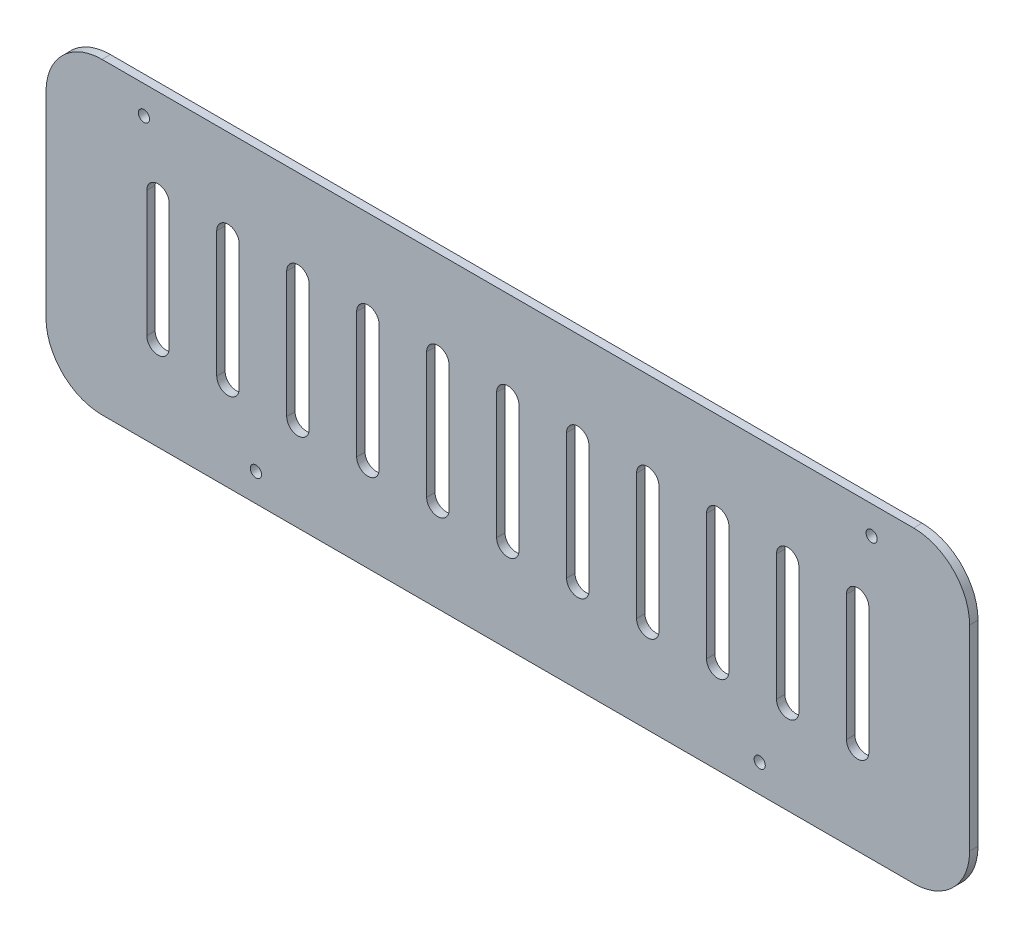
SolidWorks part; units mm, degrees
ref_plane "前视基准面" through (0, 0, 0) normal (0, 0, 1) x (1, 0, 0)
ref_plane "上视基准面" through (0, 0, 0) normal (0, 1, 0) x (1, 0, 0)
ref_plane "右视基准面" through (0, 0, 0) normal (1, 0, 0) x (0, 0, -1)
sketch "草图2" plane through (0, 0, 0) normal (0, 0, 1) x (1, 0, 0)
  line L0 (20.1153, 69.9959) -> (20.1153, -40.0041) construction
  line L1 (-144.8847, 69.9959) -> (185.1153, 69.9959)
  line L2 (-144.8847, 69.9959) -> (-144.8847, -40.0041)
  line L3 (-144.8847, -40.0041) -> (185.1153, -40.0041)
  line L4 (185.1153, 69.9959) -> (185.1153, -40.0041)
  circle A0 centre (-109.8847, 59.9959) radius 2
  circle A1 centre (150.1153, 59.9959) radius 2
  circle A2 centre (-69.8847, -30.0041) radius 2
  circle A3 centre (110.1153, -30.0041) radius 2
  dimension "D3" = 4
  dimension "D6" = 4
  dimension "D1" = 330
  dimension "D2" = 110
  dimension "D4" = 10
  dimension "D5" = 130
  dimension "D7" = 10
  dimension "D8" = 90
  dimension "D9" = 90
extrude "凸台-拉伸1" add sketch "草图2" along normal blind 3
sketch "草图3" plane through (0, 0, 3) normal (0, 0, 1) x (1, 0, 0)
  line L0 (20.1153, 69.9959) -> (20.1153, -40.0041) construction
  line L1 (185.1153, 69.9959) -> (-144.8847, 69.9959) construction
  line L2 (-144.8847, -40.0041) -> (185.1153, -40.0041) construction
  line L3 (20.1153, -7.5041) -> (20.1153, 37.4959) construction
  line L4 (16.1153, -7.5041) -> (16.1153, 37.4959)
  line L5 (24.1153, -7.5041) -> (24.1153, 37.4959)
  line L6 (45.1153, -7.5041) -> (45.1153, 37.4959) construction
  line L7 (41.1153, -7.5041) -> (41.1153, 37.4959)
  line L8 (49.1153, -7.5041) -> (49.1153, 37.4959)
  line L9 (70.1153, -7.5041) -> (70.1153, 37.4959) construction
  line L10 (66.1153, -7.5041) -> (66.1153, 37.4959)
  line L11 (74.1153, -7.5041) -> (74.1153, 37.4959)
  line L12 (95.1153, -7.5041) -> (95.1153, 37.4959) construction
  line L13 (91.1153, -7.5041) -> (91.1153, 37.4959)
  line L14 (99.1153, -7.5041) -> (99.1153, 37.4959)
  line L15 (120.1153, -7.5041) -> (120.1153, 37.4959) construction
  line L16 (116.1153, -7.5041) -> (116.1153, 37.4959)
  line L17 (124.1153, -7.5041) -> (124.1153, 37.4959)
  line L18 (145.1153, -7.5041) -> (145.1153, 37.4959) construction
  line L19 (141.1153, -7.5041) -> (141.1153, 37.4959)
  line L20 (149.1153, -7.5041) -> (149.1153, 37.4959)
  line L21 (-4.8847, -7.5041) -> (-4.8847, 37.4959) construction
  line L22 (-0.8847, -7.5041) -> (-0.8847, 37.4959)
  line L23 (-8.8847, -7.5041) -> (-8.8847, 37.4959)
  line L24 (-29.8847, -7.5041) -> (-29.8847, 37.4959) construction
  line L25 (-25.8847, -7.5041) -> (-25.8847, 37.4959)
  line L26 (-33.8847, -7.5041) -> (-33.8847, 37.4959)
  line L27 (-54.8847, -7.5041) -> (-54.8847, 37.4959) construction
  line L28 (-50.8847, -7.5041) -> (-50.8847, 37.4959)
  line L29 (-58.8847, -7.5041) -> (-58.8847, 37.4959)
  line L30 (-79.8847, -7.5041) -> (-79.8847, 37.4959) construction
  line L31 (-75.8847, -7.5041) -> (-75.8847, 37.4959)
  line L32 (-83.8847, -7.5041) -> (-83.8847, 37.4959)
  line L33 (-104.8847, -7.5041) -> (-104.8847, 37.4959) construction
  line L34 (-100.8847, -7.5041) -> (-100.8847, 37.4959)
  line L35 (-108.8847, -7.5041) -> (-108.8847, 37.4959)
  arc A0 (16.1153, -7.5041) -> (24.1153, -7.5041) centre (20.1153, -7.5041) ccw
  arc A1 (24.1153, 37.4959) -> (16.1153, 37.4959) centre (20.1153, 37.4959) ccw
  arc A2 (41.1153, -7.5041) -> (49.1153, -7.5041) centre (45.1153, -7.5041) ccw
  arc A3 (49.1153, 37.4959) -> (41.1153, 37.4959) centre (45.1153, 37.4959) ccw
  arc A4 (66.1153, -7.5041) -> (74.1153, -7.5041) centre (70.1153, -7.5041) ccw
  arc A5 (74.1153, 37.4959) -> (66.1153, 37.4959) centre (70.1153, 37.4959) ccw
  arc A6 (91.1153, -7.5041) -> (99.1153, -7.5041) centre (95.1153, -7.5041) ccw
  arc A7 (99.1153, 37.4959) -> (91.1153, 37.4959) centre (95.1153, 37.4959) ccw
  arc A8 (116.1153, -7.5041) -> (124.1153, -7.5041) centre (120.1153, -7.5041) ccw
  arc A9 (124.1153, 37.4959) -> (116.1153, 37.4959) centre (120.1153, 37.4959) ccw
  arc A10 (141.1153, -7.5041) -> (149.1153, -7.5041) centre (145.1153, -7.5041) ccw
  arc A11 (149.1153, 37.4959) -> (141.1153, 37.4959) centre (145.1153, 37.4959) ccw
  arc A12 (-0.8847, -7.5041) -> (-8.8847, -7.5041) centre (-4.8847, -7.5041) cw
  arc A13 (-8.8847, 37.4959) -> (-0.8847, 37.4959) centre (-4.8847, 37.4959) cw
  arc A14 (-25.8847, -7.5041) -> (-33.8847, -7.5041) centre (-29.8847, -7.5041) cw
  arc A15 (-33.8847, 37.4959) -> (-25.8847, 37.4959) centre (-29.8847, 37.4959) cw
  arc A16 (-50.8847, -7.5041) -> (-58.8847, -7.5041) centre (-54.8847, -7.5041) cw
  arc A17 (-58.8847, 37.4959) -> (-50.8847, 37.4959) centre (-54.8847, 37.4959) cw
  arc A18 (-75.8847, -7.5041) -> (-83.8847, -7.5041) centre (-79.8847, -7.5041) cw
  arc A19 (-83.8847, 37.4959) -> (-75.8847, 37.4959) centre (-79.8847, 37.4959) cw
  arc A20 (-100.8847, -7.5041) -> (-108.8847, -7.5041) centre (-104.8847, -7.5041) cw
  arc A21 (-108.8847, 37.4959) -> (-100.8847, 37.4959) centre (-104.8847, 37.4959) cw
  point P8 (20.1153, 14.9959)
  point P17 (45.1153, 14.9959)
  point P24 (70.1153, 14.9959)
  point P31 (95.1153, 14.9959)
  point P38 (120.1153, 14.9959)
  point P45 (145.1153, 14.9959)
  point P50 (-4.8847, 14.9959)
  point P57 (-29.8847, 14.9959)
  point P64 (-54.8847, 14.9959)
  point P71 (-79.8847, 14.9959)
  point P78 (-104.8847, 14.9959)
  dimension "D2" = 4
  dimension "D1" = 45
  dimension "D3" = 6
extrude "切除-拉伸1" cut sketch "草图3" against normal through all
fillet "圆角1" radius 20 4 edges at (185.1153, -40.0041, 1.5) (185.1153, 69.9959, 1.5) (-144.8847, -40.0041, 1.5) (-144.8847, 69.9959, 1.5)
